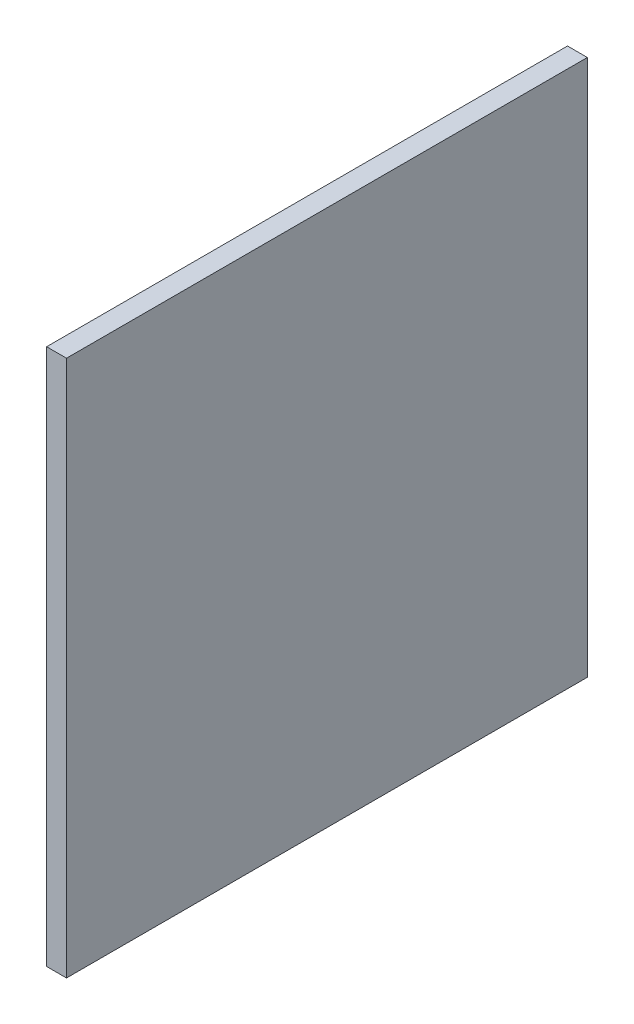
SolidWorks part; units mm, degrees
ref_plane "Front Plane" through (0, 0, 0) normal (0, 0, 1) x (1, 0, 0)
ref_plane "Top Plane" through (0, 0, 0) normal (0, 1, 0) x (1, 0, 0)
ref_plane "Right Plane" through (0, 0, 0) normal (1, 0, 0) x (0, 0, -1)
sketch "Sketch1" plane through (0, 0, 0) normal (1, 0, 0) x (0, 0, -1)
  line L1 (33.274, -34.29) -> (-33.274, -34.29)
  line L2 (33.274, -34.29) -> (33.274, 34.29)
  line L3 (33.274, 34.29) -> (-33.274, 34.29)
  line L4 (-33.274, -34.29) -> (-33.274, 34.29)
  line L5 (33.274, -34.29) -> (-33.274, 34.29) construction
  line L6 (33.274, 34.29) -> (-33.274, -34.29) construction
  point P0 (0, 0)
  dimension "D1" = 68.58
  dimension "D2" = 66.548
extrude "Boss-Extrude1" add sketch "Sketch1" along normal blind 2.54
sketch "Sketch2" plane through (0, 0, 0) normal (-1, 0, 0) x (0, 0, 1)
  text T0 "Instrument Board" font "Century Gothic" height in points 18
extrude "Boss-Extrude2" add sketch "Sketch2" along normal blind 2.54
